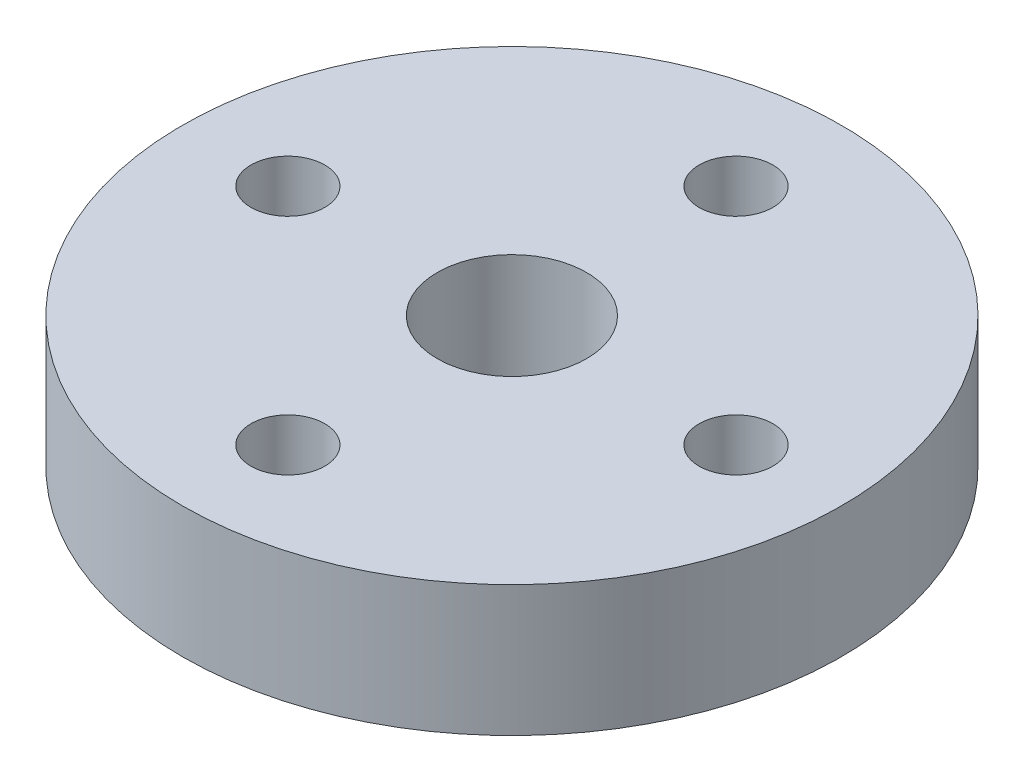
SolidWorks part; units mm, degrees
ref_plane "Front Plane" through (0, 0, 0) normal (0, 0, 1) x (1, 0, 0)
ref_plane "Top Plane" through (0, 0, 0) normal (0, 1, 0) x (1, 0, 0)
ref_plane "Right Plane" through (0, 0, 0) normal (1, 0, 0) x (0, 0, -1)
sketch "Sketch1" plane through (0, 0, 0) normal (0, 1, 0) x (1, 0, 0)
  line L0 (0, 17.65) -> (0, -17.65) construction
  line L1 (-17.65, 0) -> (17.65, 0) construction
  circle A0 centre (0, 0) radius 17.65
  circle A1 centre (0, 0) radius 4
  circle A2 centre (0, 12) radius 1.975
  circle A3 centre (12, 0) radius 1.975
  circle A4 centre (0, -12) radius 1.975
  circle A5 centre (-12, 0) radius 1.975
  point P19 (0, 0)
  dimension "D1" = 35.3
  dimension "D2" = 8
  dimension "D3" = 12
  dimension "D4" = 3.95
  dimension "D5" = 4
extrude "Boss-Extrude1" add sketch "Sketch1" along normal blind 7
